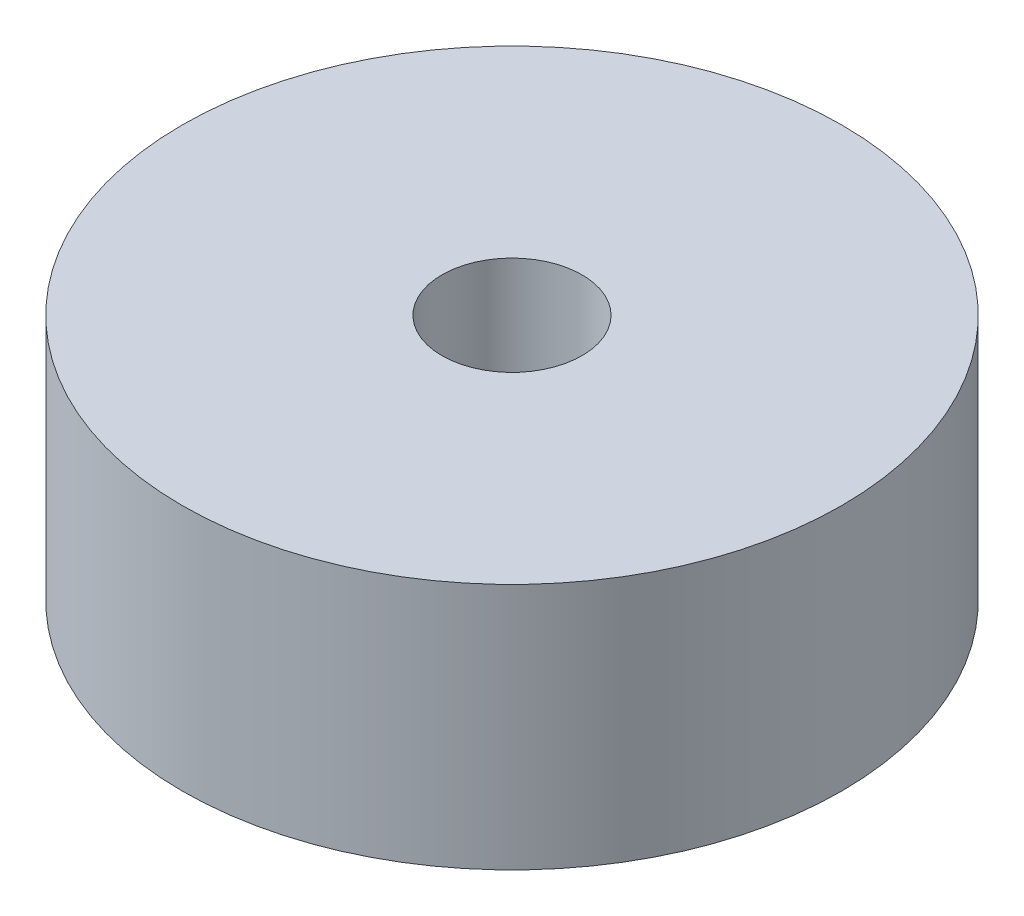
SolidWorks part; units mm, degrees
ref_plane "前视基准面" through (0, 0, 0) normal (0, 0, 1) x (1, 0, 0)
ref_plane "上视基准面" through (0, 0, 0) normal (0, 1, 0) x (1, 0, 0)
ref_plane "右视基准面" through (0, 0, 0) normal (1, 0, 0) x (0, 0, -1)
other "Configuration Table"
sketch "草图1" plane through (0, 0, 0) normal (0, 1, 0) x (1, 0, 0)
  line L1 (-5, 5) -> (5, 5) construction
  line L2 (-5, 5) -> (-5, -5) construction
  line L3 (-5, -5) -> (5, -5) construction
  line L4 (5, 5) -> (5, -5) construction
  line L5 (-5, 5) -> (5, -5) construction
  line L6 (-5, -5) -> (5, 5) construction
  circle A0 centre (0, 0) radius 1.7
  circle A1 centre (0, 0) radius 8
  dimension "D1" = 3.4
  dimension "D2" = 16
  dimension "D3" = 10
  dimension "D4" = 10
extrude "凸台-拉伸1" add sketch "草图1" along normal blind 6
